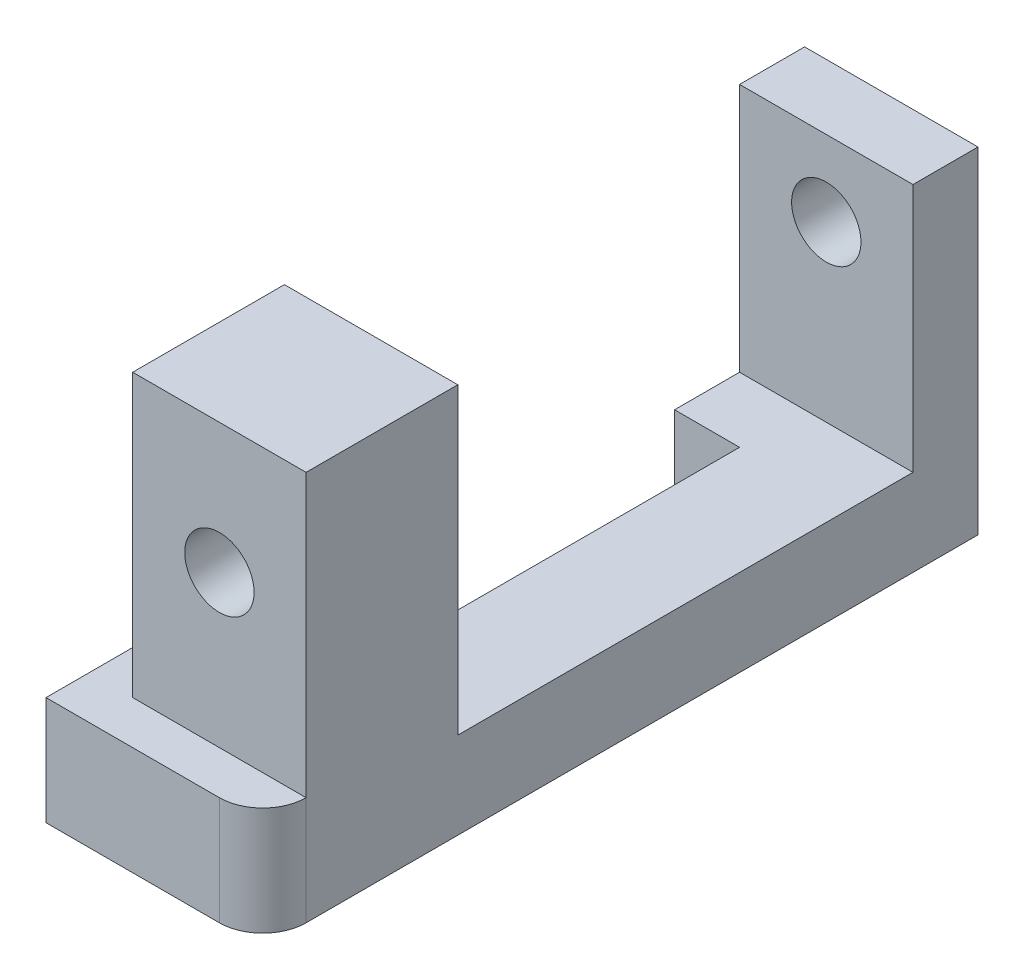
SolidWorks part; units mm, degrees
ref_plane "Front Plane" through (0, 0, 0) normal (0, 0, 1) x (1, 0, 0)
ref_plane "Top Plane" through (0, 0, 0) normal (0, 1, 0) x (1, 0, 0)
ref_plane "Right Plane" through (0, 0, 0) normal (1, 0, 0) x (0, 0, -1)
sketch "Sketch1" plane through (0, 0, 0) normal (1, 0, 0) x (0, 0, -1)
  line L0 (0, 0) -> (0, 16)
  line L1 (0, 16) -> (-3, 16)
  line L2 (-3, 16) -> (-3, 4)
  line L3 (-3, 4) -> (-24, 4)
  line L4 (-24, 4) -> (-24, 18)
  line L5 (-24, 18) -> (-31, 18)
  line L6 (-31, 18) -> (-31, 0)
  line L7 (-31, 0) -> (0, 0)
  dimension "D1" = 3
  dimension "D2" = 16
  dimension "D3" = 12
  dimension "D4" = 18
  dimension "D5" = 31
  dimension "D6" = 7
extrude "Boss-Extrude1" add sketch "Sketch1" against normal blind 8
sketch "Sketch3" plane through (-8, 0, 0) normal (-1, 0, 0) x (0, 0, 1)
  line L0 (3, 16) -> (3, 4) construction
  line L1 (3, 4) -> (24, 4)
  line L2 (3, 4) -> (3, 0)
  line L3 (3, 0) -> (24, 0)
  line L4 (24, 4) -> (24, 0)
  line L5 (24, 4) -> (24, 18) construction
  line L6 (31, 0) -> (0, 0) construction
  line L7 (3, 4) -> (24, 4) construction
extrude "Cut-Extrude1" [suppressed] cut sketch "Sketch3" against normal blind 4
sketch "Sketch5" plane through (0, 0, 3) normal (0, 0, 1) x (1, 0, 0)
  line L0 (-8, 0) -> (-3, 0)
  line L1 (-8, 0) -> (0, 0) construction
  line L2 (-3, 0) -> (-5, 4)
  line L3 (-5, 4) -> (-8, 4)
  line L4 (-8, 18) -> (-8, 0) construction
  line L5 (-8, 4) -> (-8, 0)
  dimension "D1" = 5
  dimension "D2" = 3
  dimension "D3" = 4
extrude "Cut-Extrude2" cut sketch "Sketch5" along normal up to surface (21 mm away) up to face at (-4, 11, 24)
sketch "Sketch6" plane through (0, 0, 31) normal (0, 0, 1) x (1, 0, 0)
  line L0 (0, 18) -> (0, 0) construction
  line L1 (-8, 0) -> (0, 0) construction
  circle A0 centre (-4, 12) radius 1.6
  dimension "D1" = 3.2
  dimension "D2" = 4
  dimension "D3" = 12
sketch "Sketch8" plane through (0, 0, 3) normal (0, 0, 1) x (1, 0, 0)
  line L0 (-8, 4) -> (-5, 4)
  line L1 (-5, 4) -> (-3, 0)
  line L2 (-3, 0) -> (-8, 0)
  line L3 (-8, 0) -> (-8, 4)
extrude "Boss-Extrude2" add sketch "Sketch8" along normal blind 3
sketch "Sketch11" plane through (0, 0, 0) normal (0, -1, 0) x (1, 0, 0)
  line L0 (-3, 24) -> (-8, 24) construction
  line L2 (-10, 26) -> (-10, 33)
  line L3 (-10, 33) -> (-2, 33)
  line L4 (0, 31) -> (-8, 31)
  line L5 (-8, 31) -> (-8, 24)
  line L6 (-8, 31) -> (0, 31) construction
  line L7 (0, 31) -> (0, 0) construction
  arc A0 (-2, 33) -> (0, 31) centre (-2, 31) cw
  arc A1 (-10, 26) -> (-8, 24) centre (-8, 26) ccw
  dimension "D1" = 2
  dimension "D2" = 2
extrude "Boss-Extrude5" add sketch "Sketch11" against normal blind 5
extrude "Cut-Extrude3" cut sketch "Sketch6" against normal through all
sketch "Sketch12" plane through (0, 16, 0) normal (0, 1, 0) x (1, 0, 0)
  line L1 (0, -3) -> (-8, -3)
  line L2 (0, -3) -> (0, 0)
  line L3 (0, 0) -> (-8, 0)
  line L4 (-8, -3) -> (-8, 0)
extrude "Cut-Extrude4" cut sketch "Sketch12" against normal blind 0.5
